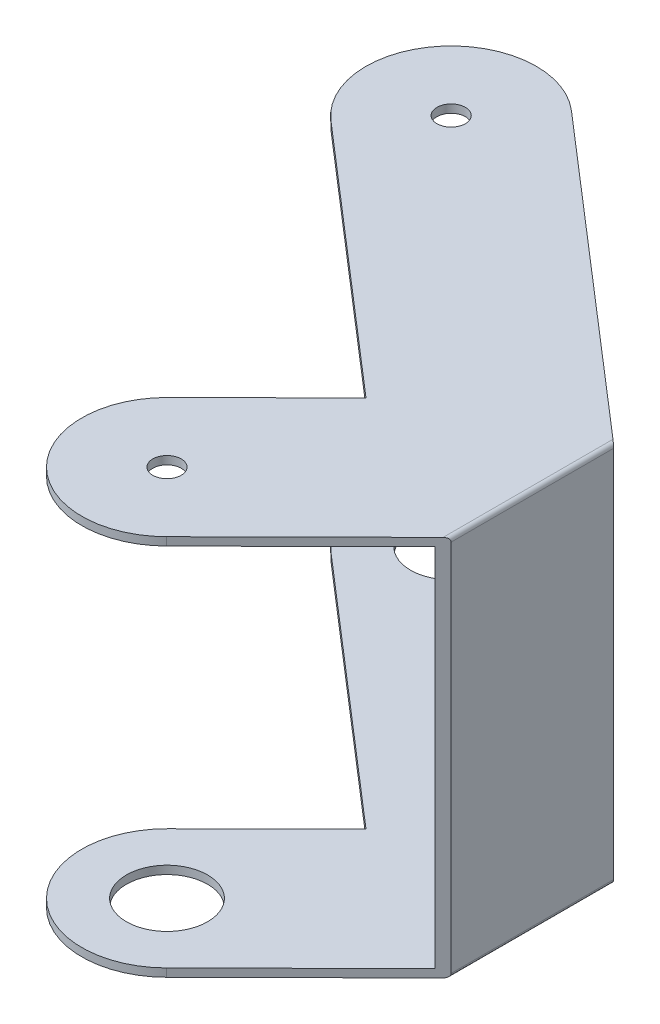
SolidWorks part; units mm, degrees
ref_plane "前视基准面" through (0, 0, 0) normal (0, 0, 1) x (1, 0, 0)
ref_plane "上视基准面" through (0, 0, 0) normal (0, 1, 0) x (1, 0, 0)
ref_plane "右视基准面" through (0, 0, 0) normal (1, 0, 0) x (0, 0, -1)
sketch "草图1" plane through (0, 0, 0) normal (0, 1, 0) x (1, 0, 0)
  line L0 (-40.0467, 0) -> (48.9586, 0) construction
  line L1 (0, 28.6211) -> (0, -29.5351) construction
  line L2 (-45.8336, 55) -> (67.8169, 55) construction
  line L3 (25, 30) -> (84.2704, 30) construction
  line L5 (25, 30) -> (-13.1358, 62.9456)
  line L6 (25, 10) -> (7.3926, -7.4565)
  line L7 (-26.8642, 47.0544) -> (4.8835, 19.6274)
  line L8 (-7.3926, 7.4565) -> (4.8835, 19.6274)
  line L10 (25, 30) -> (25, 10)
  arc A0 (-7.3926, 7.4565) -> (7.3926, -7.4565) centre (0, 0) ccw
  arc A1 (-13.1358, 62.9456) -> (-26.8642, 47.0544) centre (-20, 55) ccw
  dimension "D1" = 20
  dimension "D3" = 21
  dimension "D4" = 21
  dimension "D2" = 55
  dimension "D8" = 45
extrude "凸台-拉伸1" add sketch "草图1" along normal blind 47 contours L7 L8 A0 L6 L10 L5 A1
shell "抽壳1" thickness 1
fillet "圆角2" radius 0.5 2 edges at (25, 0, -20) (25, 47, -20)
hole_wizard "Ø3.5 (3.5) 直径槽口1" positions "草图4" profile "草图5" size "Ø3.5" standard "GB"
sketch "草图4" plane through (0, 47, 0) normal (0, 1, 0) x (1, 0, 0)
  line L0 (24.5, 30.432) -> (-13.1358, 62.9456) construction
  point P0 (0, 0)
  point P3 (-20, 55)
  dimension "D1" = 10.5
sketch "草图5" plane through (0, 47, 0) normal (1, 0, 0) x (0, 0, 1)
  line L0 (0, 0) -> (0, 1)
  line L1 (0, 1) -> (1.75, 1)
  line L2 (1.75, 1) -> (1.75, 0)
  line L5 (1.75, 0) -> (0, 0)
  line L11 (0, -6.35) -> (0, 107.95) construction
  dimension "通孔孔直径" = 3.5
  dimension "通孔孔深度" = 1
hole_wizard "Ø10.0 (10) 直径槽口3" positions "草图6" profile "草图7" size "Ø10.0" standard "GB"
sketch "草图6" plane through (0, 0, 0) normal (0, -1, 0) x (-1, 0, 0)
  line L2 (26.8642, 47.0544) -> (-4.8835, 19.6274) construction
  line L3 (-27.9177, 30) -> (-91.1625, 30) construction
  point P0 (0, 0)
  point P3 (20, 55)
  point P30 (0, 0)
  dimension "D1" = 25
  dimension "D2" = 10.5
sketch "草图7" plane through (0, 0, 0) normal (1, 0, 0) x (0, 0, -1)
  line L0 (0, 0) -> (0, 1)
  line L1 (0, 1) -> (5, 1)
  line L2 (5, 1) -> (5, 0)
  line L5 (5, 0) -> (0, 0)
  line L11 (0, -6.35) -> (0, 107.95) construction
  dimension "通孔孔直径" = 10
  dimension "通孔孔深度" = 1
